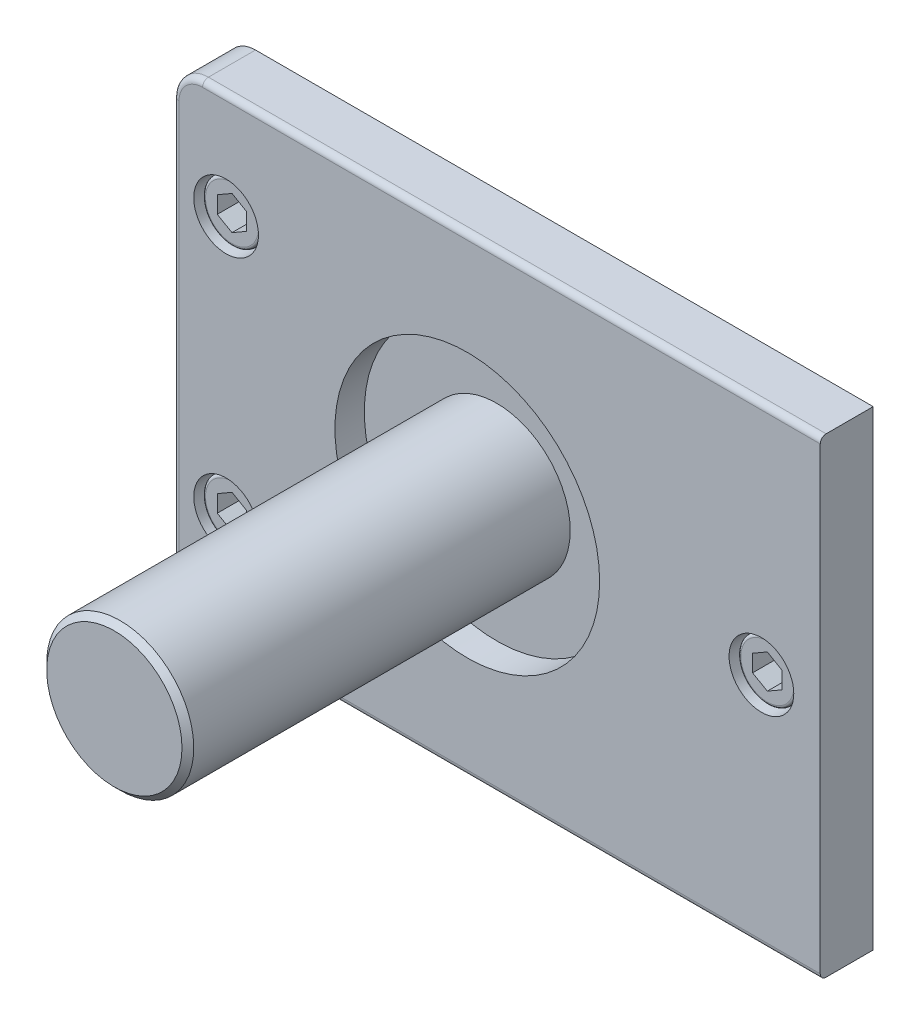
SolidWorks part; units mm, degrees
ref_plane "Plan de face" through (0, 0, 0) normal (0, 0, 1) x (1, 0, 0)
ref_plane "Plan de dessus" through (0, 0, 0) normal (0, 1, 0) x (1, 0, 0)
ref_plane "Plan de droite" through (0, 0, 0) normal (1, 0, 0) x (0, 0, -1)
sketch "Esquisse1" plane through (0, 0, 0) normal (0, 0, 1) x (-1, 0, 0)
  line L8 (0, 5) -> (0, 75)
  line L9 (-5, 80) -> (-110, 80)
  line L10 (-110, 80) -> (-110, 0)
  line L11 (-110, 0) -> (-5, 0)
  arc A4 (0, 75) -> (-5, 80) centre (-5, 75) ccw
  arc A5 (-5, 0) -> (0, 5) centre (-5, 5) ccw
extrude "Boss.-Extru.1" add sketch "Esquisse1" along normal blind 9
fillet "Congé1" radius 1 5 edges at (57.5, -80, 9) (1.4645, -78.5355, 9) (0, -40, 9) (57.5, 0, 9) (1.4645, -1.4645, 9)
sketch "Esquisse2" plane through (0, 0, 0) normal (0, 0, -1) x (1, 0, 0)
  circle A2 centre (9, 18) radius 3.3235
  circle A3 centre (6, 40) radius 3
  circle A4 centre (9, 62) radius 3.3235
  circle A5 centre (50, 40) radius 38
  circle A6 centre (100, 40) radius 3.3235
sketch "Esquisse4" plane through (0, 0, 9) normal (0, 0, 1) x (1, 0, 0)
  circle A0 centre (9, -18) radius 5.5
  dimension "D1" = 11
extrude "Enlèv. mat.-Extru.1" cut sketch "Esquisse4" against normal blind 7
sketch "Esquisse5" plane through (0, 0, 2) normal (0, 0, 1) x (1, 0, 0)
  circle A0 centre (9, -18) radius 5
  dimension "D1" = 10
extrude "Boss.-Extru.2" add sketch "Esquisse5" along normal blind 6
fillet "Congé2" radius 0.5 1 edges at (14, -18, 8)
sketch "Esquisse6" plane through (0, 0, 8) normal (0, 0, 1) x (1, 0, 0)
  line L0 (9, -15.1132) -> (9, -20.8868) construction
  line L1 (9, -15.1132) -> (6.5, -16.5566)
  line L2 (6.5, -16.5566) -> (6.5, -19.4434)
  line L3 (6.5, -19.4434) -> (9, -20.8868)
  line L4 (9, -20.8868) -> (11.5, -19.4434)
  line L5 (11.5, -19.4434) -> (11.5, -16.5566)
  line L6 (11.5, -16.5566) -> (9, -15.1132)
  circle A0 centre (9, -18) radius 2.5 construction
  dimension "D1" = 5
extrude "Enlèv. mat.-Extru.2" cut sketch "Esquisse6" against normal blind 4
pattern_linear "Répétition linéaire1" count 2 spacing 44 along (0, -1, 0) of "Enlèv. mat.-Extru.1", "Boss.-Extru.2", "Congé2", "Enlèv. mat.-Extru.2"
sketch "Esquisse7" plane through (0, 0, 9) normal (0, 0, 1) x (1, 0, 0)
  circle A0 centre (100, -40) radius 5.5
  dimension "D1" = 11
extrude "Enlèv. mat.-Extru.3" cut sketch "Esquisse7" against normal blind 7
sketch "Esquisse8" plane through (0, 0, 2) normal (0, 0, 1) x (1, 0, 0)
  circle A0 centre (100, -40) radius 5
  dimension "D1" = 10
extrude "Boss.-Extru.3" add sketch "Esquisse8" along normal blind 6
fillet "Congé3" radius 0.5 1 edges at (105, -40, 8)
sketch "Esquisse9" plane through (0, 0, 8) normal (0, 0, 1) x (1, 0, 0)
  line L1 (100, -37.1132) -> (97.5, -38.5566)
  line L2 (97.5, -38.5566) -> (97.5, -41.4434)
  line L3 (97.5, -41.4434) -> (100, -42.8868)
  line L4 (100, -42.8868) -> (102.5, -41.4434)
  line L5 (102.5, -41.4434) -> (102.5, -38.5566)
  line L6 (102.5, -38.5566) -> (100, -37.1132)
  circle A0 centre (100, -40) radius 2.5 construction
  dimension "D1" = 5
extrude "Enlèv. mat.-Extru.4" cut sketch "Esquisse9" against normal blind 5
sketch "Esquisse10" plane through (0, 0, 0) normal (0, 0, -1) x (-1, 0, 0)
  circle A0 centre (-6, -40) radius 3
extrude "Enlèv. mat.-Extru.5" cut sketch "Esquisse10" against normal blind 5
sketch "Esquisse11" plane through (0, 0, 9) normal (0, 0, 1) x (1, 0, 0)
  circle A0 centre (50, -40) radius 15
  dimension "D1" = 30
extrude "Enlèv. mat.-Extru.6" [suppressed] cut sketch "Esquisse11" against normal through all
sketch "Esquisse12" plane through (0, 0, 9) normal (0, 0, 1) x (1, 0, 0)
  line L0 (5, 0) -> (110, 0) construction
  line L2 (0, -75) -> (0, -5) construction
  circle A0 centre (50, -40) radius 22.5
  dimension "D1" = 45
  dimension "D3" = 50
  dimension "D2" = 40
extrude "Enlèv. mat.-Extru.7" cut sketch "Esquisse12" against normal blind 5
sketch "Esquisse14" plane through (0, 0, 4) normal (0, 0, 1) x (1, 0, 0)
  circle A0 centre (50, -40) radius 12.5
  dimension "D1" = 25
extrude "Boss.-Extru.4" add sketch "Esquisse14" along normal blind 65
chamfer "Chanfrein1" distance 1 angle 45 1 edges at (62.5, -40, 69)
